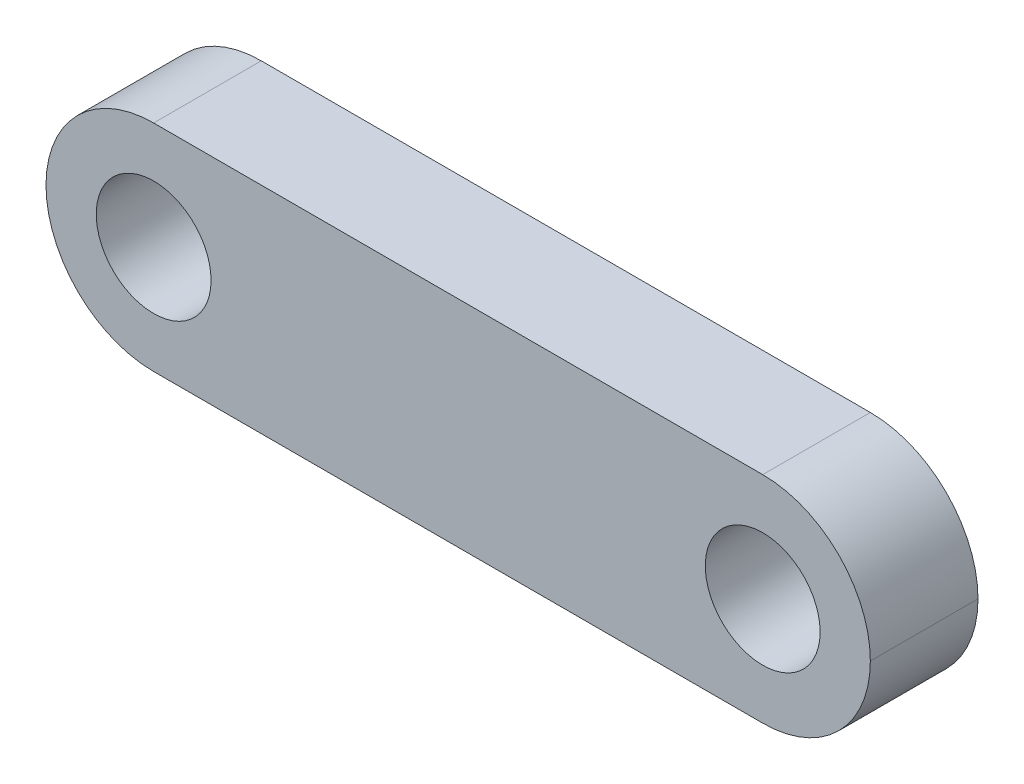
SolidWorks part; units mm, degrees
ref_plane "前视基准面" through (0, 0, 0) normal (0, 0, 1) x (1, 0, 0)
ref_plane "上视基准面" through (0, 0, 0) normal (0, 1, 0) x (1, 0, 0)
ref_plane "右视基准面" through (0, 0, 0) normal (1, 0, 0) x (0, 0, -1)
ref_plane "基准面4" through (0, 0, 3) normal (0, 0, 1) x (1, 0, 0)
sketch "草图1" plane through (0, 0, 3) normal (0, 0, 1) x (1, 0, 0)
  line L0 (7.7741, 5.999) -> (-9.2001, 5.999)
  line L1 (-9.2001, 0) -> (7.7741, 0)
  arc A0 (10.7741, 3) -> (7.7741, 5.999) centre (7.7741, 2.999) ccw
  arc A1 (-9.2001, 5.999) -> (-12.2001, 2.999) centre (-9.2001, 2.999) ccw
  arc A2 (-12.2001, 2.999) -> (-9.2001, 0) centre (-9.2001, 3) ccw
  arc A3 (7.7741, 0) -> (10.7741, 3) centre (7.7741, 3) ccw
  circle A4 centre (7.7741, 3) radius 1.35
  circle A5 centre (-9.2001, 3) radius 1.35
extrude "凸台-拉伸1" add sketch "草图1" against normal blind 3
sketch "草图2" plane through (0, 0, 3) normal (0, 0, 1) x (1, 0, 0)
  circle A0 centre (-9.2001, 3) radius 1.6
  circle A1 centre (7.7741, 2.999) radius 1.6
  dimension "D1" = 3.2
extrude "切除-拉伸1" cut sketch "草图2" against normal through all
